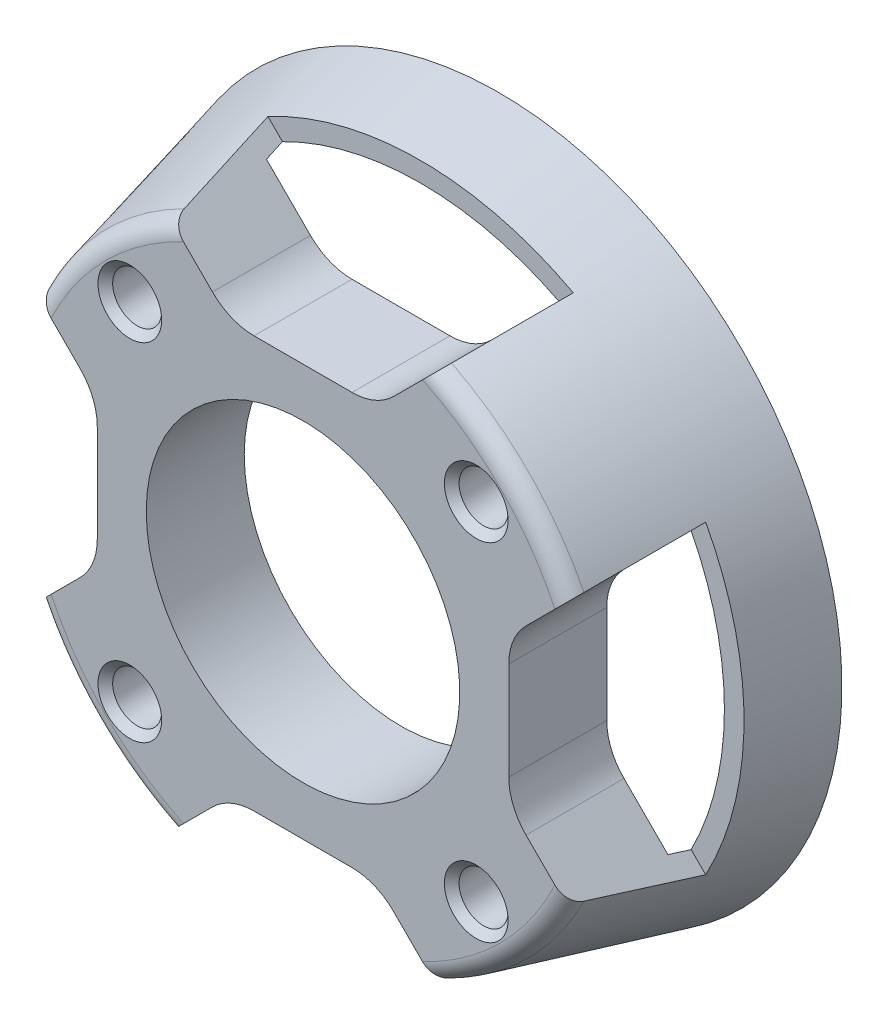
SolidWorks part; units mm, degrees
material "6061-T6 (SS)"
ref_plane "Front Plane" through (0, 0, 0) normal (0, 0, 1) x (1, 0, 0)
ref_plane "Top Plane" through (0, 0, 0) normal (0, 1, 0) x (1, 0, 0)
ref_plane "Right Plane" through (0, 0, 0) normal (1, 0, 0) x (0, 0, -1)
sketch "Sketch4" plane through (0, 0, 0) normal (1, 0, 0) x (0, 0, -1)
  line L0 (0, 0) -> (-13.8652, 0) construction
  line L1 (0, 16.5) -> (0, 17.5)
  line L2 (0, 17.5) -> (-10, 15.0067)
  line L3 (-10, 15.0067) -> (-10, 8)
  line L4 (-10, 8) -> (-5, 8)
  line L5 (-10.3515, 14) -> (-10.3515, 11) construction
  line L6 (-5, 8) -> (-5, 15.2534)
  line L7 (-5, 15.2534) -> (0, 16.5)
  point P10 (-10.3515, 12.5)
  dimension "D1" = 35
  dimension "D2" = 10
  dimension "D3" = 3
  dimension "D4" = 25
  dimension "D5" = 1
  dimension "D6" = 76
  dimension "D7" = 5
  dimension "D8" = 16
revolve "Revolve1" add sketch "Sketch4" angle 360 about L0
sketch "Hole pattern" plane through (0, 0, 10) normal (0, 0, 1) x (1, 0, 0)
  line L1 (-8.8388, -8.8388) -> (8.8388, -8.8388)
  line L2 (-8.8388, -8.8388) -> (-8.8388, 8.8388)
  line L3 (-8.8388, 8.8388) -> (8.8388, 8.8388)
  line L4 (8.8388, -8.8388) -> (8.8388, 8.8388)
  line L5 (-8.8388, -8.8388) -> (8.8388, 8.8388) construction
  line L6 (-8.8388, 8.8388) -> (8.8388, -8.8388) construction
  point P0 (0, 0)
  dimension "D1" = 25
fillet "Fillet1" radius 1 1 edges at (-15.0067, 0, 10)
hole_wizard "M3x0.5 Tapped Hole1" positions "Sketch6" profile "Sketch8" tap size "M3x0.5" standard "ANSI Metric" end condition through all
sketch "Sketch6" plane through (0, 0, 10) normal (0, 0, 1) x (1, 0, 0)
  point P0 (8.8388, 8.8388)
  point P3 (-8.8388, 8.8388)
  point P6 (-8.8388, -8.8388)
  point P9 (8.8388, -8.8388)
sketch "Sketch8" plane through (8.8388, 8.8388, 10) normal (1, 0, 0) x (0, -1, 0)
  line L0 (0, 0) -> (0, 10)
  line L1 (0, 10) -> (1.25, 10)
  line L2 (1.25, 10) -> (1.25, 0.375)
  line L3 (1.25, 0.375) -> (1.625, 0)
  line L5 (1.625, 0) -> (0, 0)
  line L6 (-1.25, 0.375) -> (-1.625, 0) construction
  line L11 (0, -6.35) -> (0, 107.95) construction
  dimension "Thru Tap Drill Dia." = 2.5
  dimension "Thru Tap Drill Depth" = 10
  dimension "Near C'Sink Dia." = 3.25
  dimension "Near C'Sink Angle" = 90
cosmetic thread "Hole Thread1" parameters "D2"=3
cosmetic thread "Hole Thread2" parameters "D2"=3
cosmetic thread "Hole Thread3" parameters "D2"=3
cosmetic thread "Hole Thread4" parameters "D2"=3
sketch "Sketch9" plane through (0, 0, 10) normal (0, 0, 1) x (1, 0, 0)
  line L0 (-13.2426, 20) -> (-4.6213, 11.3787)
  line L1 (-2.5, 10.5) -> (2.5, 10.5)
  line L2 (0, 10.5) -> (0, 0) construction
  line L3 (13.2426, 20) -> (4.6213, 11.3787)
  line L4 (-13.2426, 20) -> (13.2426, 20)
  line L5 (20, 13.2426) -> (11.3787, 4.6213)
  line L6 (10.5, 2.5) -> (10.5, -2.5)
  line L7 (20, -13.2426) -> (11.3787, -4.6213)
  line L8 (20, 13.2426) -> (20, -13.2426)
  line L9 (13.2426, -20) -> (4.6213, -11.3787)
  line L10 (2.5, -10.5) -> (-2.5, -10.5)
  line L11 (-13.2426, -20) -> (-4.6213, -11.3787)
  line L12 (13.2426, -20) -> (-13.2426, -20)
  line L13 (-20, -13.2426) -> (-11.3787, -4.6213)
  line L14 (-10.5, -2.5) -> (-10.5, 2.5)
  line L15 (-20, 13.2426) -> (-11.3787, 4.6213)
  line L16 (-20, -13.2426) -> (-20, 13.2426)
  arc A0 (-4.6213, 11.3787) -> (-2.5, 10.5) centre (-2.5, 13.5) ccw
  arc A1 (4.6213, 11.3787) -> (2.5, 10.5) centre (2.5, 13.5) cw
  arc A2 (11.3787, 4.6213) -> (10.5, 2.5) centre (13.5, 2.5) ccw
  arc A3 (11.3787, -4.6213) -> (10.5, -2.5) centre (13.5, -2.5) cw
  arc A4 (4.6213, -11.3787) -> (2.5, -10.5) centre (2.5, -13.5) ccw
  arc A5 (-4.6213, -11.3787) -> (-2.5, -10.5) centre (-2.5, -13.5) cw
  arc A6 (-11.3787, -4.6213) -> (-10.5, -2.5) centre (-13.5, -2.5) ccw
  arc A7 (-11.3787, 4.6213) -> (-10.5, 2.5) centre (-13.5, 2.5) cw
  point P0 (0, 0)
  point P40 (0, 0)
  dimension "D5" = 3
  dimension "D1" = 20
  dimension "D2" = 10.5
  dimension "D3" = 45
  dimension "D4" = 9.5563
  dimension "D7" = 5
  dimension "D6" = 4
extrude "Cut-Extrude1" cut sketch "Sketch9" against normal blind 6
